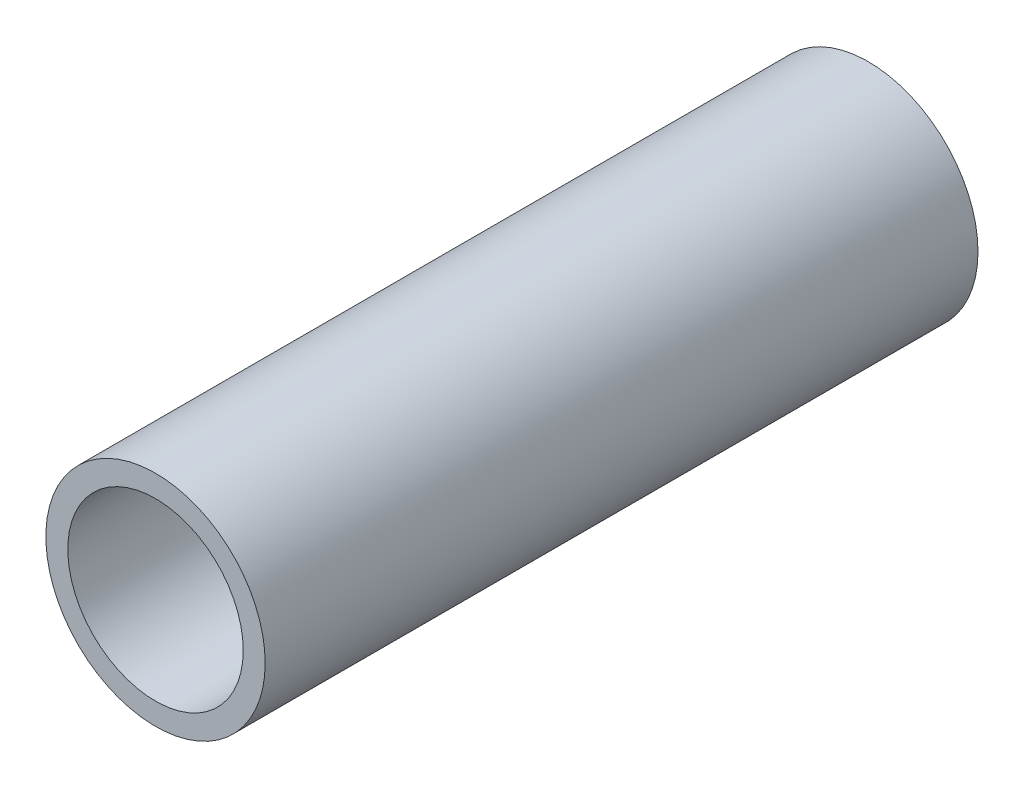
SolidWorks part; units mm, degrees
material "Thornel Mat VMA"
ref_plane "前视基准面" through (0, 0, 0) normal (0, 0, 1) x (1, 0, 0)
ref_plane "上视基准面" through (0, 0, 0) normal (0, 1, 0) x (1, 0, 0)
ref_plane "右视基准面" through (0, 0, 0) normal (1, 0, 0) x (0, 0, -1)
other "Configuration Table"
sketch "草图1" plane through (0, 0, 0) normal (0, 0, 1) x (1, 0, 0)
  circle A0 centre (0, 0) radius 10
  circle A1 centre (0, 0) radius 8
  dimension "D1" = 20
extrude "凸台-拉伸1" add sketch "草图1" along normal blind 65
